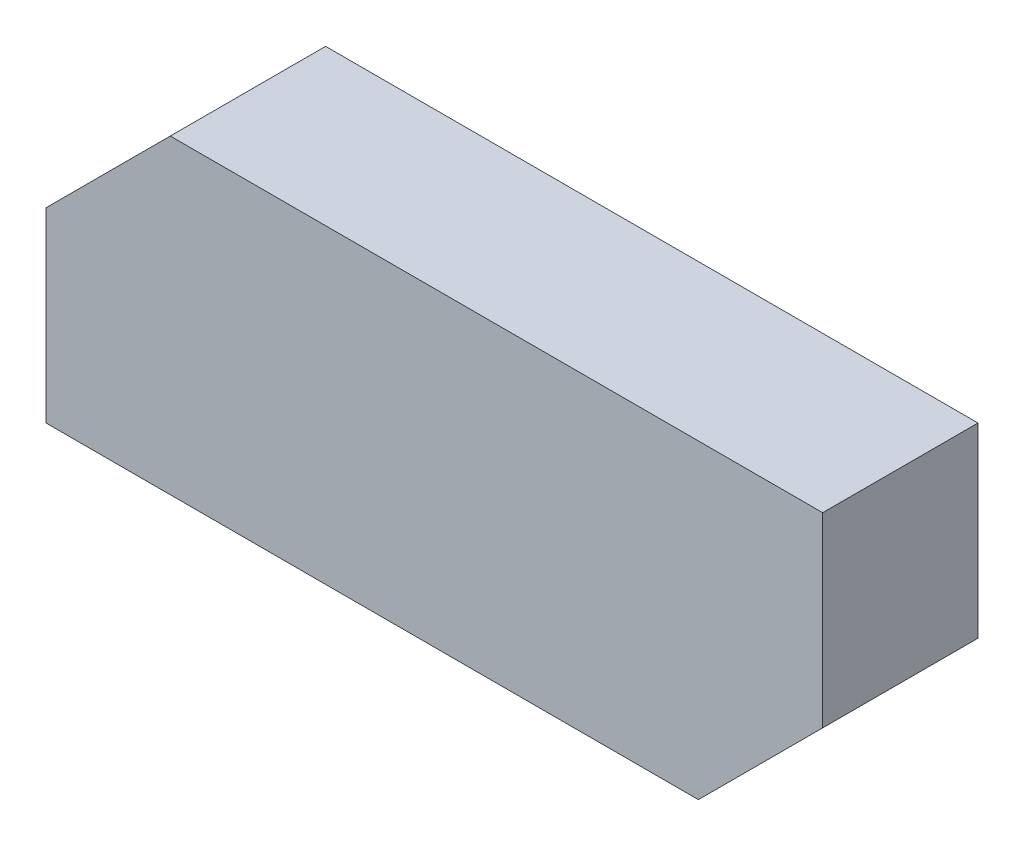
SolidWorks part; units mm, degrees
material "Q355"
ref_plane "前视基准面" through (0, 0, 0) normal (0, 0, 1) x (1, 0, 0)
ref_plane "上视基准面" through (0, 0, 0) normal (0, 1, 0) x (1, 0, 0)
ref_plane "右视基准面" through (0, 0, 0) normal (1, 0, 0) x (0, 0, -1)
sketch "草图1" plane through (0, 0, 0) normal (0, 0, 1) x (1, 0, 0)
  line L1 (-25, 10) -> (25, 10)
  line L2 (-25, 10) -> (-25, -10)
  line L3 (-25, -10) -> (25, -10)
  line L4 (25, 10) -> (25, -10)
  line L5 (-25, 10) -> (25, -10) construction
  line L6 (-25, -10) -> (25, 10) construction
  point P0 (0, 0)
  dimension "D1" = 50
  dimension "D2" = 20
extrude "凸台-拉伸1" add sketch "草图1" along normal blind 10
chamfer "倒角1" distance 8 angle 45 2 edges at (25, -10, 5) (-25, 10, 5)
